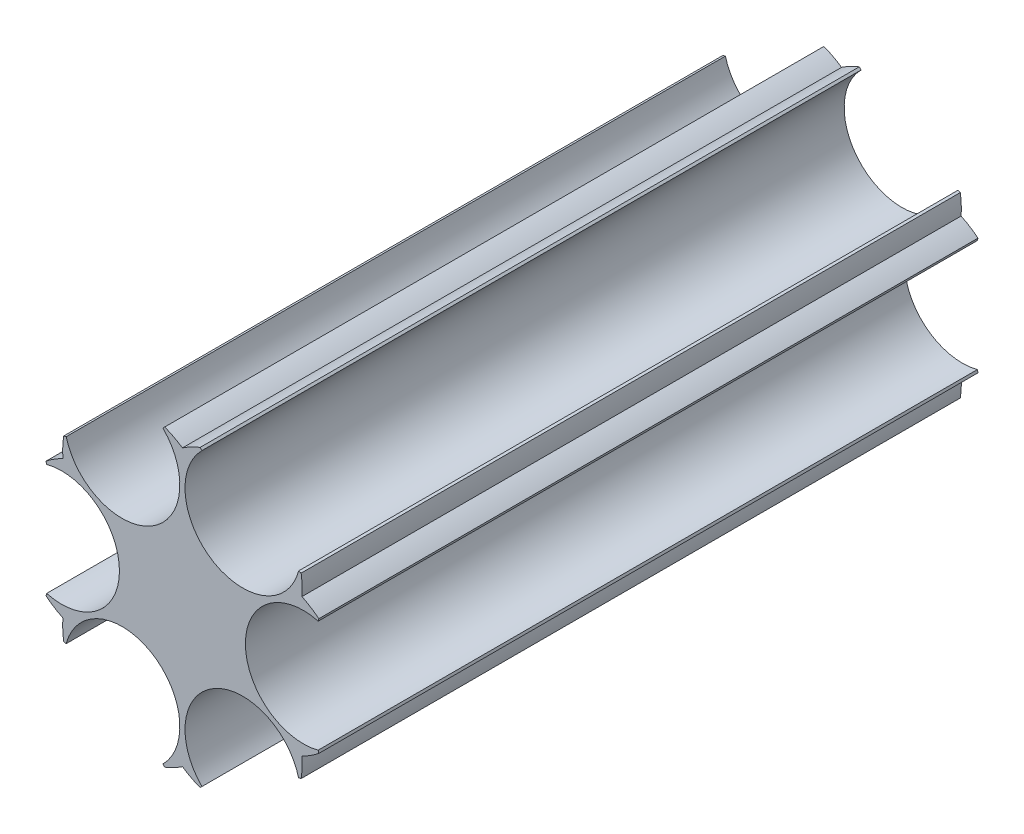
SolidWorks part; units mm, degrees
ref_plane "Plan de face" through (0, 0, 0) normal (0, 0, 1) x (1, 0, 0)
ref_plane "Plan de dessus" through (0, 0, 0) normal (0, 1, 0) x (1, 0, 0)
ref_plane "Plan de droite" through (0, 0, 0) normal (1, 0, 0) x (0, 0, -1)
sketch "Esquisse1" plane through (0, 0, 0) normal (0, 0, 1) x (1, 0, 0)
  line L0 (-35, 0) -> (35, 0) construction
  line L2 (0, 0) -> (0, -53.5) construction
  line L3 (-39.5293, 16.9037) -> (-39.3352, 16.1793)
  line L4 (-31.4635, 18.3063) -> (31.5363, 18.1806) construction
  line L5 (-31.4635, 18.3063) -> (-31.4137, 43.3063) construction
  line L6 (-31.4137, 43.3063) -> (31.5862, 43.1806) construction
  line L7 (31.5363, 18.1806) -> (31.5862, 43.1806) construction
  line L8 (-39.3352, 16.1793) -> (-35, 0) construction
  line L9 (-35, 0) -> (-39.3352, -16.1793) construction
  line L10 (-39.5293, -16.9037) -> (-39.3352, -16.1793)
  line L17 (-34.6353, -19.9967) -> (0, 0) construction
  line L19 (-34.4037, 25.7816) -> (-33.6793, 25.9757)
  line L20 (-5.1256, 42.6853) -> (-5.656, 42.1549)
  line L21 (5.1256, 42.6853) -> (5.656, 42.1549)
  line L22 (34.4037, 25.7816) -> (33.6793, 25.9757)
  line L23 (39.5293, 16.9037) -> (39.3352, 16.1793)
  line L24 (39.5293, -16.9037) -> (39.3352, -16.1793)
  line L25 (34.4037, -25.7816) -> (33.6793, -25.9757)
  line L26 (5.1256, -42.6853) -> (5.656, -42.1549)
  line L27 (-5.1256, -42.6853) -> (-5.656, -42.1549)
  line L28 (-34.4037, -25.7816) -> (-33.6793, -25.9757)
  circle A0 centre (0, 0) radius 17.5 construction
  circle A1 centre (35, 0) radius 17.5 construction
  circle A2 centre (-35, 0) radius 17.5 construction
  circle A3 centre (-17.5, -30.3109) radius 17.5 construction
  circle A4 centre (17.5, -30.3109) radius 17.5 construction
  circle A6 centre (0, 0) radius 53.5 construction
  circle A7 centre (0, 0) radius 16.75 construction
  circle A8 centre (35, 0) radius 16.75 construction
  circle A9 centre (-35, 0) radius 16.75 construction
  circle A10 centre (-17.5, -30.3109) radius 16.75 construction
  circle A11 centre (17.5, -30.3109) radius 16.75 construction
  arc A12 (-39.3352, 16.1793) -> (-39.3352, -16.1793) centre (-35, 0) cw
  arc A17 (-39.5293, -16.9037) -> (-34.6353, -19.9967) centre (-23.8162, 2.541) ccw
  arc A24 (-39.5293, 16.9037) -> (-34.6353, 19.9967) centre (-23.8162, -2.541) cw
  arc A25 (-34.4037, 25.7816) -> (-34.6353, 19.9967) centre (-9.7075, 21.896) ccw
  arc A26 (-5.656, 42.1549) -> (-33.6793, 25.9757) centre (-17.5, 30.3109) cw
  arc A27 (-5.1256, 42.6853) -> (0, 39.9933) centre (-14.1087, 19.3549) cw
  arc A28 (5.1256, 42.6853) -> (0, 39.9933) centre (14.1087, 19.3549) ccw
  arc A29 (33.6793, 25.9757) -> (5.656, 42.1549) centre (17.5, 30.3109) cw
  arc A30 (34.4037, 25.7816) -> (34.6353, 19.9967) centre (9.7075, 21.896) cw
  arc A31 (39.5293, 16.9037) -> (34.6353, 19.9967) centre (23.8162, -2.541) ccw
  arc A32 (39.3352, -16.1793) -> (39.3352, 16.1793) centre (35, 0) cw
  arc A33 (39.5293, -16.9037) -> (34.6353, -19.9967) centre (23.8162, 2.541) cw
  arc A34 (34.4037, -25.7816) -> (34.6353, -19.9967) centre (9.7075, -21.896) ccw
  arc A35 (5.656, -42.1549) -> (33.6793, -25.9757) centre (17.5, -30.3109) cw
  arc A36 (5.1256, -42.6853) -> (0, -39.9933) centre (14.1087, -19.3549) cw
  arc A37 (-5.1256, -42.6853) -> (0, -39.9933) centre (-14.1087, -19.3549) ccw
  arc A38 (-33.6793, -25.9757) -> (-5.656, -42.1549) centre (-17.5, -30.3109) cw
  arc A39 (-34.4037, -25.7816) -> (-34.6353, -19.9967) centre (-9.7075, -21.896) cw
  point P12 (-36.7439, 19.9238)
  point P27 (0, 0)
  point P48 (0, 0)
  point P61 (0, 0)
  point P80 (0, 0)
  dimension "D1" = 35
  dimension "D2" = 6
  dimension "D5" = 33.5
  dimension "D6" = 32.3585
  dimension "D7" = 150
  dimension "D9" = 20
  dimension "D11" = 25
  dimension "D3" = 63
  dimension "D4" = 25
extrude "Boss.-Extru.1" add sketch "Esquisse1" along normal blind 191
